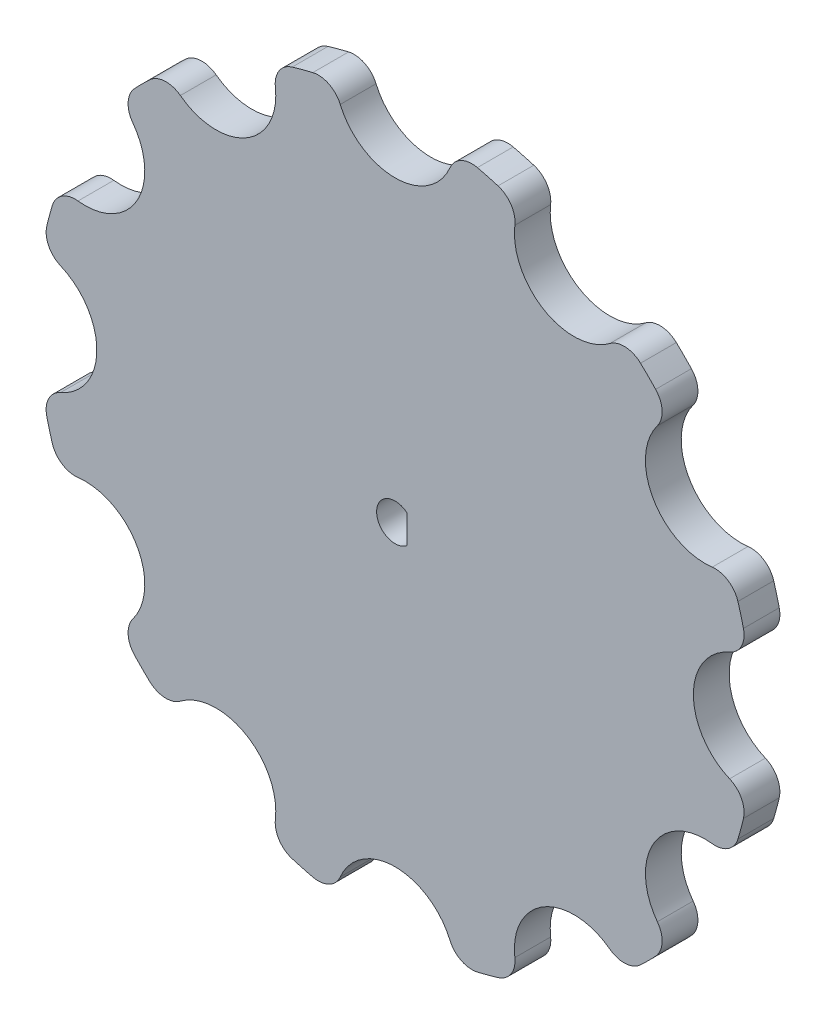
SolidWorks part; units mm, degrees
ref_plane "Front Plane" through (0, 0, 0) normal (0, 0, 1) x (1, 0, 0)
ref_plane "Top Plane" through (0, 0, 0) normal (0, 1, 0) x (1, 0, 0)
ref_plane "Right Plane" through (0, 0, 0) normal (1, 0, 0) x (0, 0, -1)
sketch "Sketch1" plane through (0, 0, 0) normal (0, 0, 1) x (1, 0, 0)
  line L0 (0, 25) -> (0, 30) construction
  circle A0 centre (0, 0) radius 30
  circle A1 centre (0, 0) radius 25 construction
  circle A2 centre (0, 30) radius 5
  circle A3 centre (15, 25.9808) radius 5
  circle A4 centre (25.9808, 15) radius 5
  circle A5 centre (30, 0) radius 5
  circle A6 centre (25.9808, -15) radius 5
  circle A7 centre (15, -25.9808) radius 5
  circle A8 centre (0, -30) radius 5
  circle A9 centre (-15, -25.9808) radius 5
  circle A10 centre (-25.9808, -15) radius 5
  circle A11 centre (-30, 0) radius 5
  circle A12 centre (-25.9808, 15) radius 5
  circle A13 centre (-15, 25.9808) radius 5
  point P31 (0, 0)
  dimension "D1" = 60
  dimension "D2" = 50
  dimension "D3" = 12
extrude "Boss-Extrude1" add sketch "Sketch1" along normal blind 3 contours A13 A0 A12 A11 A10 A9 A8 A7 A6 A5 A4 A3 A2
fillet "Fillet1" radius 2 4 edges at (-23.1286, 19.1067, 1.5) (-19.1067, 23.1286, 1.5) (-10.4766, 28.1112, 1.5) (-4.9826, 29.5833, 1.5)
fillet "Fillet2" radius 2 20 edges at (-28.1112, 10.4766, 1.5) (-29.5833, -4.9826, 1.5) (-29.5833, 4.9826, 1.5) (-23.1286, -19.1067, 1.5) (-28.1112, -10.4766, 1.5) (-10.4766, -28.1112, 1.5) (-19.1067, -23.1286, 1.5) (4.9826, -29.5833, 1.5) (-4.9826, -29.5833, 1.5) (19.1067, -23.1286, 1.5) (10.4766, -28.1112, 1.5) (28.1112, -10.4766, 1.5) (23.1286, -19.1067, 1.5) (29.5833, 4.9826, 1.5) (29.5833, -4.9826, 1.5) (23.1286, 19.1067, 1.5) (28.1112, 10.4766, 1.5) (10.4766, 28.1112, 1.5) (19.1067, 23.1286, 1.5) (4.9826, 29.5833, 1.5)
sketch "Sketch2" plane through (0, 0, 0) normal (0, 0, -1) x (-1, 0, 0)
  line L0 (-1.55, 0) -> (-1, 0)
  line L1 (-1, 0) -> (-1, 1.1843)
  line L2 (-1, 1.1843) -> (-1, -1.1843)
  circle A0 centre (0, 0) radius 1.55
  dimension "D1" = 3.1
  dimension "D2" = 0.55
extrude "Cut-Extrude1" cut sketch "Sketch2" against normal blind 10 contours L2 A0 L1
